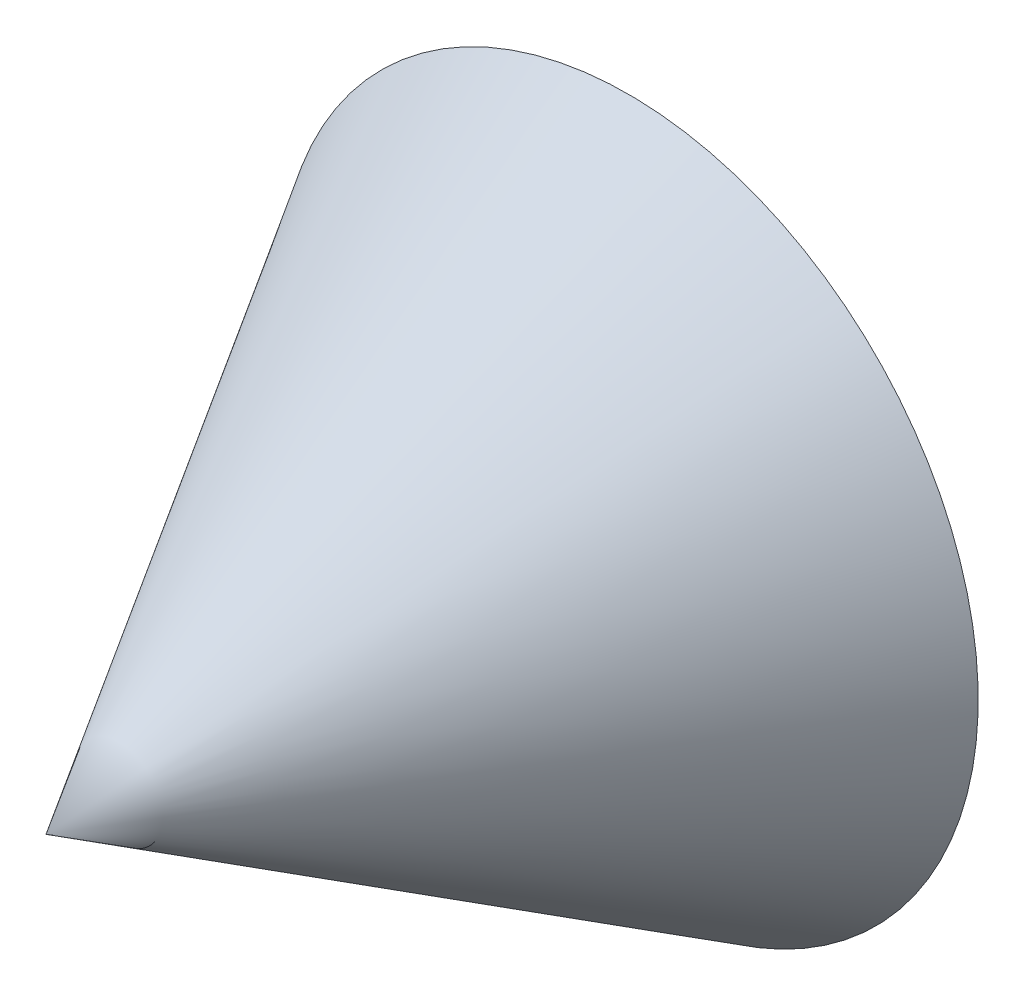
SolidWorks part; units mm, degrees
ref_plane "Front Plane" through (0, 0, 0) normal (0, 0, 1) x (1, 0, 0)
ref_plane "Top Plane" through (0, 0, 0) normal (0, 1, 0) x (1, 0, 0)
ref_plane "Right Plane" through (0, 0, 0) normal (1, 0, 0) x (0, 0, -1)
ref_plane "plane:xz" through (0, 0, 0) normal (0, -1, 0) x (1, 0, 0)
sketch "sketch:profile" plane through (0, 0, 0) normal (0, -1, 0) x (1, 0, 0)
  line L0 (0, 0) -> (6, 0)
  line L1 (6, 0) -> (0, 10)
  line L2 (0, 10) -> (0, 0)
  line L3 (0, -10) -> (0, 40) construction
revolve "feature:turn" add sketch "sketch:profile" angle 360 about L3
